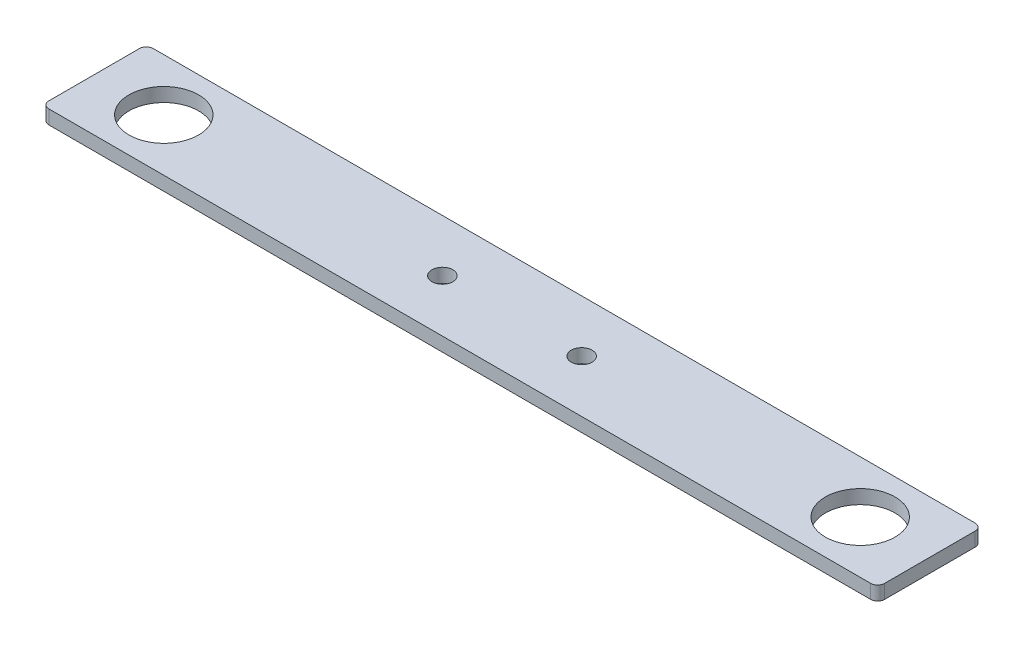
SolidWorks part; units mm, degrees
ref_plane "Front Plane" through (0, 0, 0) normal (0, 0, 1) x (1, 0, 0)
ref_plane "Top Plane" through (0, 0, 0) normal (0, 1, 0) x (1, 0, 0)
ref_plane "Right Plane" through (0, 0, 0) normal (1, 0, 0) x (0, 0, -1)
sketch "Sketch1" plane through (0, 0, 0) normal (0, 1, 0) x (1, 0, 0)
  line L0 (0, 7.5) -> (10, 7.5)
  line L1 (0, 0) -> (120, 0)
  line L2 (0, 0) -> (0, 15)
  line L3 (0, 15) -> (120, 15)
  line L4 (120, 0) -> (120, 15)
  line L5 (10, 7.5) -> (110, 7.5)
  line L6 (110, 7.5) -> (120, 7.5)
  circle A0 centre (10, 7.5) radius 5
  circle A1 centre (110, 7.5) radius 5
  circle A2 centre (50, 7.5) radius 1.5
  circle A3 centre (70, 7.5) radius 1.5
  dimension "D3" = 100
  dimension "D5" = 10
  dimension "D6" = 10
  dimension "D7" = 40
  dimension "D8" = 40
  dimension "D1" = 15
  dimension "D2" = 120
  dimension "D4" = 10
extrude "Boss-Extrude1" add sketch "Sketch1" along normal blind 2 contours A1 L5 A0 L0 L2 L1 L4 L6 | A1 L6 L4 L3 L2 L0 A0 L5
fillet "Fillet1" radius 1 4 edges at (120, 1, -15) (120, 1, 0) (0, 1, -15) (0, 1, 0)
